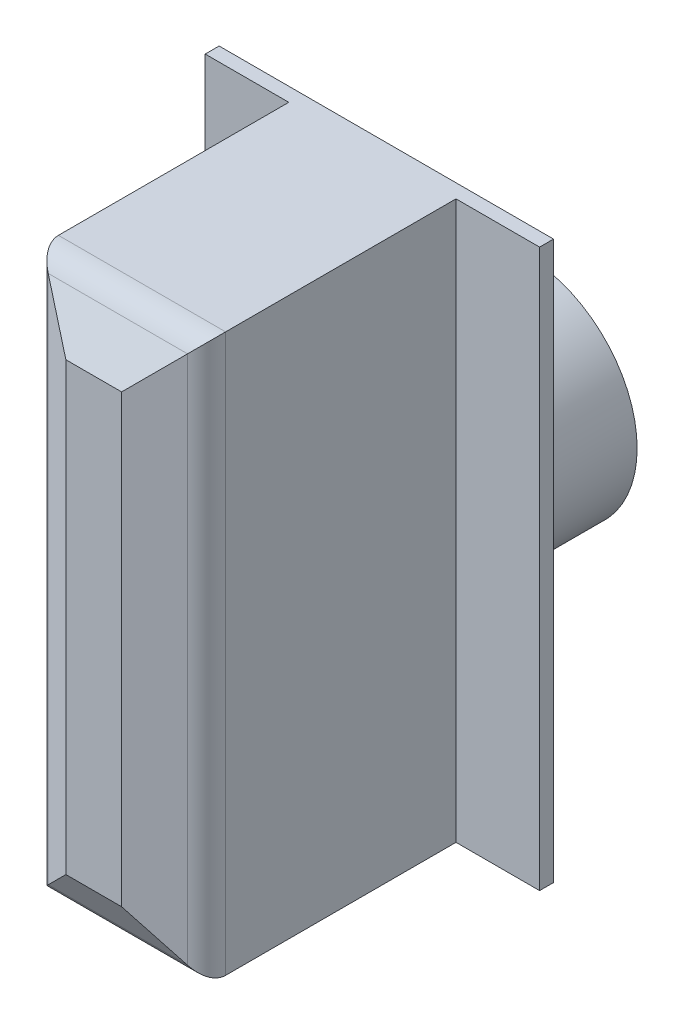
SolidWorks part; units mm, degrees
ref_plane "Front Plane" through (0, 0, 0) normal (1, 0, 0) x (0, 1, 0)
ref_plane "Top Plane" through (0, 0, 0) normal (0, 0, 1) x (0, 1, 0)
ref_plane "Right Plane" through (0, 0, 0) normal (0, 1, 0) x (-1, 0, 0)
sketch "Sketch1" plane through (0, 0, 0) normal (0, 1, 0) x (-1, 0, 0)
  line L0 (0, 1.5) -> (0, 1.75)
  line L1 (0, 1.75) -> (1.5, 1.75)
  line L2 (6, 1.75) -> (6, 1.5)
  line L8 (4.5, 1.75) -> (6, 1.75)
  line L10 (1.5, 1.75) -> (1.5, 6.75)
  line L11 (1.5, 6.75) -> (4.5, 6.75)
  line L12 (4.5, 1.75) -> (4.5, 6.75)
  line L13 (0, 1.5) -> (6, 1.5)
  dimension "D1" = 0.25
  dimension "D2" = 6
  dimension "D6" = 3
  dimension "D7" = 5
  dimension "D8" = 1.5
extrude "Boss-Extrude1" add sketch "Sketch1" along normal blind 10
chamfer "Chamfer4" distance 1 angle 30 4 edges at (-4.5, 5, 6.75) (-3, 10, 6.75) (-1.5, 5, 6.75) (-3, 0, 6.75)
fillet "Fillet3" radius 0.5 4 edges at (-3, 0, 6.1726) (-1.5, 5, 6.1726) (-3, 10, 6.1726) (-4.5, 5, 6.1726)
sketch "Sketch3" plane through (0, 0, 1.5) normal (0, 0, -1) x (1, 0, 0)
  line L0 (-6, -5) -> (0, -5) construction
  line L1 (-6, -10) -> (-6, 0) construction
  line L2 (0, -10) -> (0, 0) construction
  circle A0 centre (-3, -5) radius 1.75
  circle A1 centre (-3, -5) radius 2
  dimension "D1" = 3.5
  dimension "D2" = 4
extrude "Boss-Extrude3" add sketch "Sketch3" along normal blind 2.5
